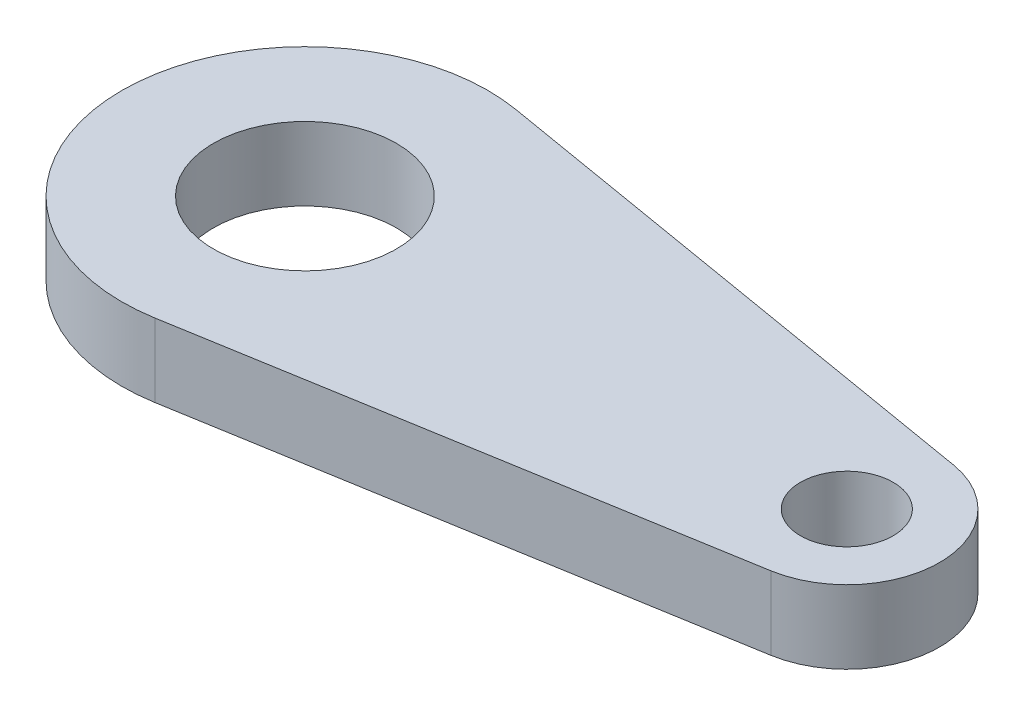
SolidWorks part; units mm, degrees
ref_plane "Front Plane" through (0, 0, 0) normal (0, 0, 1) x (1, 0, 0)
ref_plane "Top Plane" through (0, 0, 0) normal (0, 1, 0) x (1, 0, 0)
ref_plane "Right Plane" through (0, 0, 0) normal (1, 0, 0) x (0, 0, -1)
sketch "Sketch1" plane through (0, 0, 0) normal (0, 1, 0) x (1, 0, 0)
  line L0 (0, 0) -> (-56.388, 0) construction
  line L1 (-53.213, 18.7836) -> (1.6087, 9.517)
  line L2 (-53.213, -18.7836) -> (1.6087, -9.517)
  arc A0 (-53.213, 18.7836) -> (-53.213, -18.7836) centre (-56.388, 0) ccw
  circle A1 centre (-56.388, 0) radius 9.525
  circle A2 centre (0, 0) radius 4.826
  arc A3 (1.6087, -9.517) -> (1.6087, 9.517) centre (0, 0) ccw
  dimension "D2" = 38.1
  dimension "D3" = 19.05
  dimension "D4" = 19.304
  dimension "D5" = 9.652
  dimension "D1" = 56.388
extrude "Boss-Extrude1" add sketch "Sketch1" along normal blind 7.62
